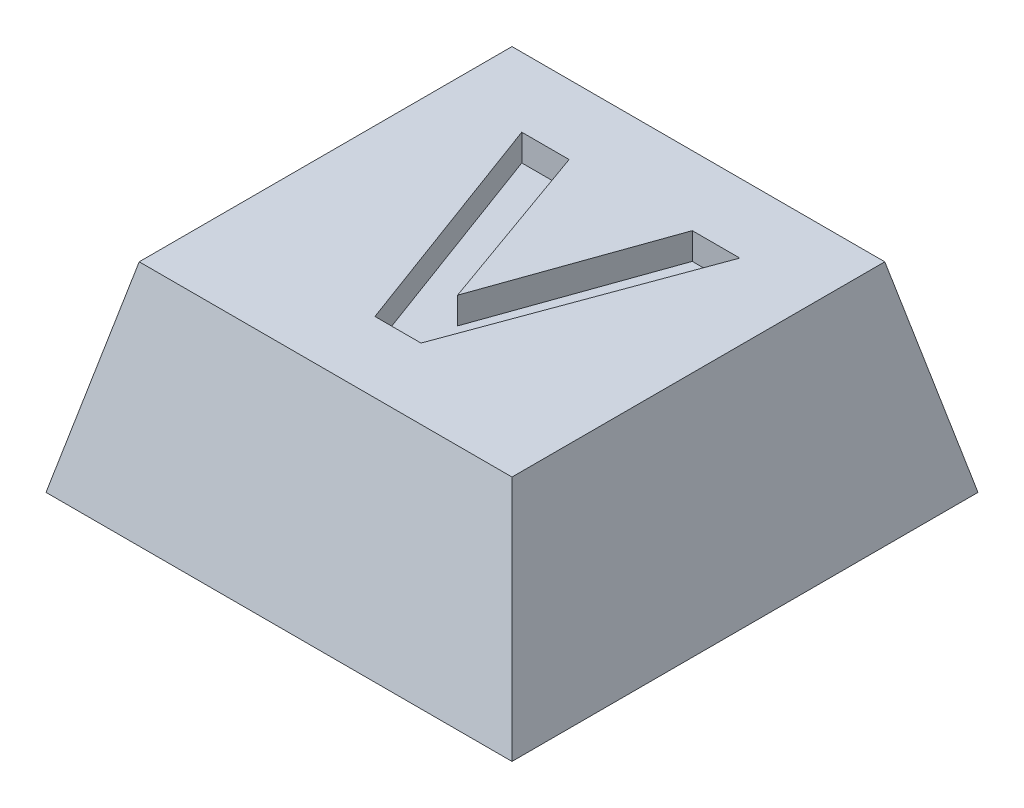
SolidWorks part; units mm, degrees
ref_plane "Front Plane" through (0, 0, 0) normal (0, 0, 1) x (1, 0, 0)
ref_plane "Top Plane" through (0, 0, 0) normal (0, 1, 0) x (1, 0, 0)
ref_plane "Right Plane" through (0, 0, 0) normal (1, 0, 0) x (0, 0, -1)
sketch "Sketch1" plane through (0, 0, 0) normal (0, 1, 0) x (1, 0, 0)
  line L1 (0, 0) -> (7, 0)
  line L2 (0, 0) -> (0, 7)
  line L3 (0, 7) -> (7, 7)
  line L4 (7, 0) -> (7, 7)
  dimension "D1" = 7
  dimension "D2" = 7
extrude "Boss-Extrude1" add sketch "Sketch1" along normal blind 3
sketch "Sketch2" plane through (0, 0, 0) normal (0, 0, 1) x (1, 0, 0)
  line L0 (0, 0) -> (0.7, 3)
  line L1 (0, 3) -> (7, 3) construction
  line L2 (0.7, 3) -> (0, 3)
  line L3 (0, 3) -> (0, 0)
  line L4 (7, 0) -> (6.3, 3)
  line L5 (6.3, 3) -> (7, 3)
  line L6 (7, 3) -> (7, 0)
  dimension "D1" = 0.7
  dimension "D2" = 0.7
extrude "Cut-Extrude1" cut sketch "Sketch2" against normal blind 7
sketch "Sketch3" plane through (0, 0, 0) normal (1, 0, 0) x (0, 0, -1)
  line L0 (0, 0) -> (0.7, 3)
  line L1 (7, 3) -> (0, 3) construction
  line L2 (0.7, 3) -> (0, 3)
  line L3 (0, 3) -> (0, 0)
  line L4 (7, 3) -> (6.3, 3)
  line L5 (6.3, 3) -> (7, 0)
  line L6 (7, 3) -> (7, 0)
  dimension "D1" = 0.7
  dimension "D2" = 0.7
extrude "Cut-Extrude2" cut sketch "Sketch3" along normal blind 11
sketch "Sketch4" plane through (0, 0, 0) normal (0, -1, 0) x (1, 0, 0)
  line L0 (3.5, 0) -> (3.5, -7) construction
  line L1 (0, 0) -> (7, 0) construction
  line L2 (7, -7) -> (0, -7) construction
  line L3 (0, -3.5) -> (7, -3.5) construction
  line L4 (0, -7) -> (0, 0) construction
  line L5 (7, 0) -> (7, -7) construction
  circle A0 centre (3.5, -3.5) radius 1.8
  dimension "D1" = 3.6
extrude "Cut-Extrude3" cut sketch "Sketch4" against normal blind 0.8
sketch "Sketch5" plane through (0, 3, 0) normal (0, 1, 0) x (1, 0, 0)
  text T0 "V" font "Arial" height 3.5
extrude "Cut-Extrude4" cut sketch "Sketch5" against normal blind 0.4
